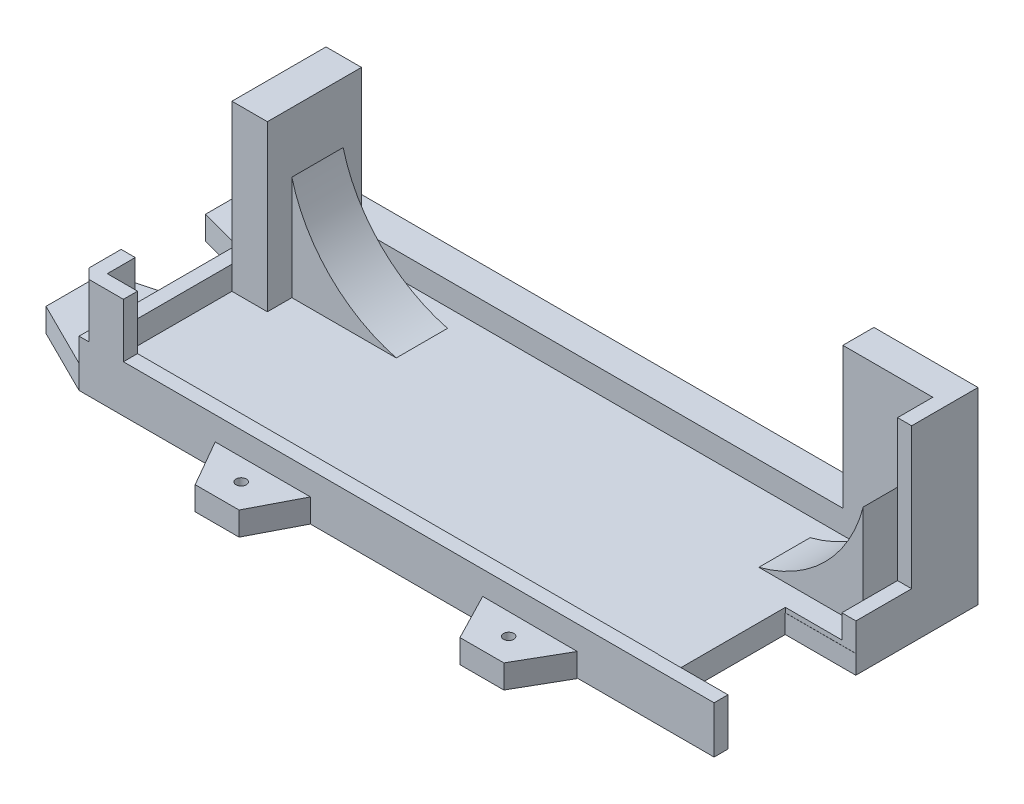
SolidWorks part; units mm, degrees
ref_plane "Front Plane" through (0, 0, 0) normal (0, 0, 1) x (1, 0, 0)
ref_plane "Top Plane" through (0, 0, 0) normal (0, 1, 0) x (1, 0, 0)
ref_plane "Right Plane" through (0, 0, 0) normal (1, 0, 0) x (0, 0, -1)
sketch "Sketch1" plane through (0, 0, 0) normal (0, 0, 1) x (1, 0, 0)
  line L0 (0, 0) -> (125, 0) construction
  line L1 (55, 0) -> (-55, 0) construction
  line L2 (0, 0) -> (-125, 0) construction
  point P5 (0, 0)
sketch "Sketch2" plane through (0, 0, 0) normal (0, 1, 0) x (1, 0, 0)
  line L0 (0, 0) -> (0, 146.5205) construction
  line L1 (-129, -27.1) -> (129, -27.1)
  line L2 (-129, -27.1) -> (-129, 65.9)
  line L3 (-129, 65.9) -> (129, 65.9)
  line L4 (129, -27.1) -> (129, 65.9)
  line L5 (0, -102.4582) -> (0, 102.4582) construction
  point P0 (0, 0)
  point P10 (0, 65.9)
  dimension "D1" = 129
  dimension "D2" = 27.1
  dimension "D3" = 65.9
sketch "Sketch3" plane through (0, 0, 0) normal (0, 1, 0) x (1, 0, 0)
  line L1 (-135, -33.1) -> (135, -33.1)
  line L2 (-135, -33.1) -> (-135, 79.1)
  line L3 (-135, 79.1) -> (135, 79.1)
  line L4 (135, -33.1) -> (135, 79.1)
  point P0 (0, 0)
  dimension "D1" = 270
  dimension "D2" = 112.2
  dimension "D3" = 33.1
extrude "Boss-Extrude1" add sketch "Sketch3" along normal blind 20
extrude "Cut-Extrude1" cut sketch "Sketch2" along normal blind 30 from offset 10
sketch "Sketch4" plane through (0, 0, 0) normal (0, 1, 0) x (1, 0, 0)
  line L1 (-135, -77.1) -> (135, -77.1)
  line L2 (-135, -77.1) -> (-135, 79.1)
  line L3 (-135, 79.1) -> (135, 79.1)
  line L4 (135, -77.1) -> (135, 79.1)
  point P0 (0, 0)
  point P7 (0, 0)
  point P8 (0, 0)
  point P9 (0, 0)
sketch "Sketch5" plane through (135, 0, 0) normal (1, 0, 0) x (0, 0, -1)
  line L0 (0, 0) -> (27.15, 0)
  line L1 (112.7288, 0) -> (-112.7288, 0) construction
  line L2 (0, 80.7562) -> (0, -80.7562) construction
  line L4 (27.15, 0) -> (27.15, 8)
  line L5 (27.15, 8) -> (0, 8)
  line L6 (0, 0) -> (0, 8)
  dimension "D1" = 8
  dimension "D2" = 27.15
extrude "Cut-Extrude2" cut sketch "Sketch5" against normal blind 30
mirror "Mirror1" about plane through (0, 0, 0) normal (0, 0, 1) of "Cut-Extrude2"
sketch "Sketch7" plane through (135, 0, 0) normal (1, 0, 0) x (0, 0, -1)
  line L1 (0, 8) -> (27.2, 8)
  line L2 (0, 8) -> (0, 20)
  line L3 (0, 20) -> (27.2, 20)
  line L4 (27.2, 8) -> (27.2, 20)
  line L5 (-33.1, 20) -> (79.1, 20) construction
  line L6 (0, 0) -> (27.2, 0) construction
  line L7 (-77.1, 0) -> (79.1, 0) construction
  line L8 (27.2, 0) -> (27.2, 20) construction
  point P4 (0, 0)
  dimension "D1" = 27.2
extrude "Cut-Extrude3" cut sketch "Sketch7" against normal blind 30
mirror "Mirror2" about plane through (0, 0, 0) normal (0, 0, 1) of "Cut-Extrude3"
sketch "Sketch23" plane through (0, 20, 0) normal (0, 1, 0) x (1, 0, 0)
  line L12 (-135, 79.1) -> (-135, -33.1) construction
  line L17 (-135, -15.2013) -> (-129, -15.2013)
  line L19 (-129, -15.2013) -> (-129, -27.1)
  line L20 (-129, -27.1) -> (-116.1295, -27.1)
  line L21 (-129, -27.1) -> (105, -27.1) construction
  line L22 (-116.1295, -27.1) -> (-116.1295, -33.1)
  line L23 (-135, -33.1) -> (135, -33.1) construction
  line L24 (-116.1295, -33.1) -> (-130.7488, -33.1)
  line L25 (-130.7488, -33.1) -> (-135, -28.8488)
  line L26 (-135, -28.8488) -> (-135, -15.2013)
  line L27 (-80.7562, 0) -> (80.7562, 0) construction
  dimension "D1" = 15.2013
extrude "Boss-Extrude6" add sketch "Sketch23" along normal blind 23
sketch "Sketch25" plane through (0, 0, 0) normal (0, 1, 0) x (1, 0, 0)
  line L0 (-135, 79.1) -> (-135, -24.7) construction
  line L1 (-135, -24.7) -> (-163, -24.7) construction
  line L2 (-163, -24.7) -> (-163, 79.1) construction
  line L3 (-163, 79.1) -> (-135, 79.1) construction
  line L4 (-135, -24.7) -> (-163, -19.1464)
  line L5 (-163, -19.1464) -> (-163, 5.7447)
  line L6 (-163, 5.7447) -> (-135, 13.2009)
  line L8 (-163, 79.1) -> (-163, -24.7) construction
  line L9 (-135, 79.1) -> (-163, 79.1) construction
  line L10 (-163, 48.6553) -> (-135, 41.1991)
  line L11 (-163, 73.5464) -> (-163, 48.6553)
  line L12 (-135, 79.1) -> (-163, 73.5464)
  line L13 (-77.113, -33.1) -> (135, -33.1) construction
  line L14 (135, -33.1) -> (135, -53.1) construction
  line L15 (135, -77.1) -> (135, 79.1) construction
  line L16 (77.113, -33.1) -> (65.6215, -53.1)
  line L17 (65.6215, -53.1) -> (46.9579, -53.1)
  line L18 (46.9579, -53.1) -> (36.6201, -33.1)
  line L20 (-46.9579, -53.1) -> (-36.6201, -33.1)
  line L21 (-65.6215, -53.1) -> (-46.9579, -53.1)
  line L22 (-77.113, -33.1) -> (-65.6215, -53.1)
  line L23 (-116.1295, -33.1) -> (135, -33.1) construction
  line L24 (135, -53.1) -> (-114.7581, -53.1) construction
  line L25 (-135, 41.1991) -> (-135, 79.1)
  line L26 (36.6201, -33.1) -> (77.113, -33.1)
  line L27 (-135, 13.2009) -> (-135, -24.7)
  line L28 (-77.113, -33.1) -> (-36.6201, -33.1)
  point P3 (0, 0)
  dimension "D1" = 28
  dimension "D2" = 20
  dimension "D3" = 103.8
  dimension "D4" = 154.226
  dimension "D5" = 93.9158
sketch "Sketch26" plane through (0, 0, 0) normal (0, 1, 0) x (1, 0, 0)
  line L0 (-135, 41.1991) -> (-135, 79.1)
  line L1 (-135, 79.1) -> (-163, 73.5464)
  line L2 (-163, 73.5464) -> (-163, 48.6553)
  line L3 (-163, 48.6553) -> (-135, 41.1991)
  line L4 (-135, 13.2009) -> (-163, 5.7447)
  line L5 (-163, 5.7447) -> (-163, -19.1464)
  line L6 (-163, -19.1464) -> (-135, -33.1)
  line L7 (-135, -33.1) -> (-135, 13.2009)
  line L8 (-77.113, -33.1) -> (-36.6201, -33.1)
  line L9 (-36.6201, -33.1) -> (-46.9579, -53.1)
  line L10 (-46.9579, -53.1) -> (-65.6215, -53.1)
  line L11 (-65.6215, -53.1) -> (-77.113, -33.1)
  line L12 (36.6201, -33.1) -> (77.0043, -33.2893)
  line L13 (77.113, -33.1) -> (65.6215, -53.1) construction
  line L14 (36.6201, -33.1) -> (46.9579, -53.1)
  line L15 (46.9579, -53.1) -> (65.6215, -53.1)
  line L16 (65.6215, -53.1) -> (77.0043, -33.2893)
extrude "Boss-Extrude7" add sketch "Sketch26" along normal blind 10
sketch "Sketch27" plane through (0, 10, 0) normal (0, 1, 0) x (1, 0, 0)
  line L0 (-135, -33.1) -> (-135, 13.2009) construction
  line L1 (-135, 13.2009) -> (-135, -9.9495) construction
  line L2 (-135, -9.9495) -> (-176.2766, -9.9495) construction
  line L3 (-135, 41.1991) -> (-135, 79.1) construction
  line L4 (-135, 79.1) -> (-135, 60.1495) construction
  line L5 (-135, 60.1495) -> (-175.0712, 60.1495) construction
  line L6 (-77.113, -33.1) -> (-36.6201, -33.1) construction
  line L7 (-36.6201, -33.1) -> (-56.8666, -33.1) construction
  line L8 (-56.8666, -33.1) -> (-56.8666, -66.7762) construction
  line L9 (36.6201, -33.1) -> (77.113, -33.1) construction
  line L10 (77.113, -33.1) -> (56.8666, -33.1) construction
  line L11 (56.8666, -33.1) -> (56.8666, -65.8523) construction
  line L12 (-56.8666, -42.31) -> (82.7467, -42.31) construction
  line L13 (56.8666, -33.1) -> (56.8666, -42.31) construction
  line L14 (-135, 60.1495) -> (-149.003, 60.1495) construction
  line L15 (-149.003, 60.1495) -> (-149.003, -39.8818) construction
  line L16 (-135, -9.9495) -> (-149.003, -9.9495) construction
  circle A0 centre (-56.8666, -42.31) radius 2.1825
  circle A1 centre (56.8666, -42.31) radius 2.1825
  circle A2 centre (-149.003, 60.1495) radius 2.1825
  circle A3 centre (-149.003, -9.9495) radius 2.1825
  dimension "D1" = 4.365
  dimension "D2" = 4.365
  dimension "D3" = 4.365
  dimension "D4" = 4.365
extrude "Cut-Extrude4" cut sketch "Sketch27" against normal mid plane 10
sketch "Sketch30" plane through (0, 10, 0) normal (0, 1, 0) x (1, 0, 0)
  line L0 (-129, -27.1) -> (121, -27.2) construction
  line L1 (105, -27.2) -> (135, -27.2) construction
  line L2 (121, -27.2) -> (121, 65.8) construction
  line L4 (129, 27.2) -> (121, 27.2)
  line L5 (129, 27.2) -> (129, 65.8)
  line L6 (129, 65.8) -> (121, 65.8)
  line L7 (121, 27.2) -> (121, 65.8)
  point P7 (0, 0)
  point P11 (129, 65.9)
  dimension "D1" = 250
  dimension "D2" = 93
sketch "Sketch31" plane through (0, 0, -65.9) normal (0, 0, 1) x (1, 0, 0)
  line L0 (0, 0) -> (0, 10) construction
  line L2 (66.6024, 72) -> (120.7328, 41.7693) construction
  line L3 (0, 10) -> (120.7328, 7.9269) construction
  line L4 (129, 10) -> (-129, 10) construction
  line L7 (0, 10) -> (0, 30) construction
  line L8 (129, 20) -> (-129, 20) construction
  line L9 (0, 30) -> (120.5861, 20) construction
  line L11 (120.7328, 41.7693) -> (129, 10)
  line L12 (129, 10) -> (66.6024, 10)
  line L15 (-4, 10) -> (0, 10) construction
  line L16 (-129, 41.7693) -> (-129, 10)
  line L17 (-129, 10) -> (-74.8695, 10)
  line L19 (-74.8695, 10) -> (-74.8695, 72) construction
  line L20 (120.7328, 7.9269) -> (120.7328, 41.7693) construction
  line L21 (0, 10) -> (129, 10) construction
  line L22 (129, 10) -> (129, 41.7693) construction
  arc A0 (66.6024, 10) -> (120.7328, 41.7693) centre (66.6024, 72) ccw
  arc A1 (-74.8695, 10) -> (-129, 41.7693) centre (-74.8695, 72) cw
  point P14 (0, 0)
  point P15 (0, 0)
  point P16 (0, 0)
  point P24 (0, 0)
  point P25 (0, 0)
  point P26 (0, 0)
  point P27 (0, 0)
  point P28 (0, 0)
  point P29 (0, 0)
  point P30 (0, 0)
  point P31 (120.7328, 7.9269)
  point P32 (0, 0)
  point P33 (129, 9.6558)
  dimension "D4" = 62
  dimension "D1" = 10
  dimension "D3" = 121
sketch "Sketch32" plane through (0, 0, -65.9) normal (0, 0, 1) x (1, 0, 0)
  line L0 (0, 0) -> (0, 10) construction
  line L1 (-129, 10) -> (121, 10) construction
  line L2 (0, -102.4582) -> (0, 102.4582) construction
  line L3 (0, 10) -> (129, 10) construction
  line L4 (129, 10) -> (-129, 10) construction
  line L5 (129, 10) -> (129, 63.2477) construction
  line L6 (0, 10) -> (7.54, 10) construction
  line L7 (129, 54.3797) -> (69.0001, 70.0007) construction
  line L8 (84.618, 10) -> (129, 10)
  line L9 (129, 10) -> (129, 54.3797)
  line L10 (84.618, 10) -> (69.0001, 70.0007) construction
  line L11 (7.54, 10) -> (7.54, 26.033) construction
  line L12 (-69.538, 10) -> (-113.92, 10)
  line L13 (-113.92, 10) -> (-113.92, 54.3797)
  line L14 (84.618, 10) -> (84.618, 127.1267) construction
  line L15 (84.618, 127.1267) -> (0, 127.1267) construction
  line L16 (0, 127.1267) -> (-107.7705, 127.1267) construction
  line L17 (-69.538, 10) -> (-69.538, 127.1267) construction
  line L18 (69.0001, 70.0007) -> (69.0001, 10) construction
  arc A0 (84.618, 10) -> (129, 54.3797) centre (69.0001, 70.0007) ccw
  arc A1 (-69.538, 10) -> (-113.92, 54.3797) centre (-53.9201, 70.0007) cw
  point P25 (129, 55.8585)
  dimension "D1" = 7.54
  dimension "D2" = 62
  dimension "D3" = 60.817
  dimension "D4" = 14.59
extrude "Boss-Extrude10" add sketch "Sketch32" along normal blind 21.8 from offset 7.8
sketch "Sketch34" plane through (0, 10, 0) normal (0, 1, 0) x (1, 0, 0)
  line L0 (-113.92, 58.1) -> (-113.92, 65.9) construction
  line L1 (129, 65.9) -> (-129, 65.9) construction
  line L2 (-113.92, 65.9) -> (-129, 65.9) construction
  line L3 (-113.92, 58.1) -> (-113.92, 25.9) construction
  line L5 (-129, 65.9) -> (-113.92, 65.9)
  line L6 (-129, 65.9) -> (-129, 25.9)
  line L7 (-129, 25.9) -> (-113.92, 25.9)
  line L8 (-113.92, 65.9) -> (-113.92, 25.9)
  dimension "D1" = 40
extrude "Boss-Extrude11" add sketch "Sketch34" along normal blind 70
sketch "Sketch36" plane through (0, 20, 0) normal (0, 1, 0) x (1, 0, 0)
  line L0 (135, 79.1) -> (135, 50.8891)
  line L1 (135, 50.8891) -> (129, 50.8891)
  line L2 (129, 36.3) -> (129, 58.1) construction
  line L3 (129, 50.8891) -> (129, 65.9)
  line L4 (129, 65.9) -> (90.7458, 65.9)
  line L5 (129, 65.9) -> (-113.92, 65.9) construction
  line L6 (90.7458, 65.9) -> (90.7458, 79.1)
  line L7 (135, 79.1) -> (-135, 79.1) construction
  line L8 (90.7458, 79.1) -> (135, 79.1)
extrude "Boss-Extrude12" add sketch "Sketch36" along normal blind 60
